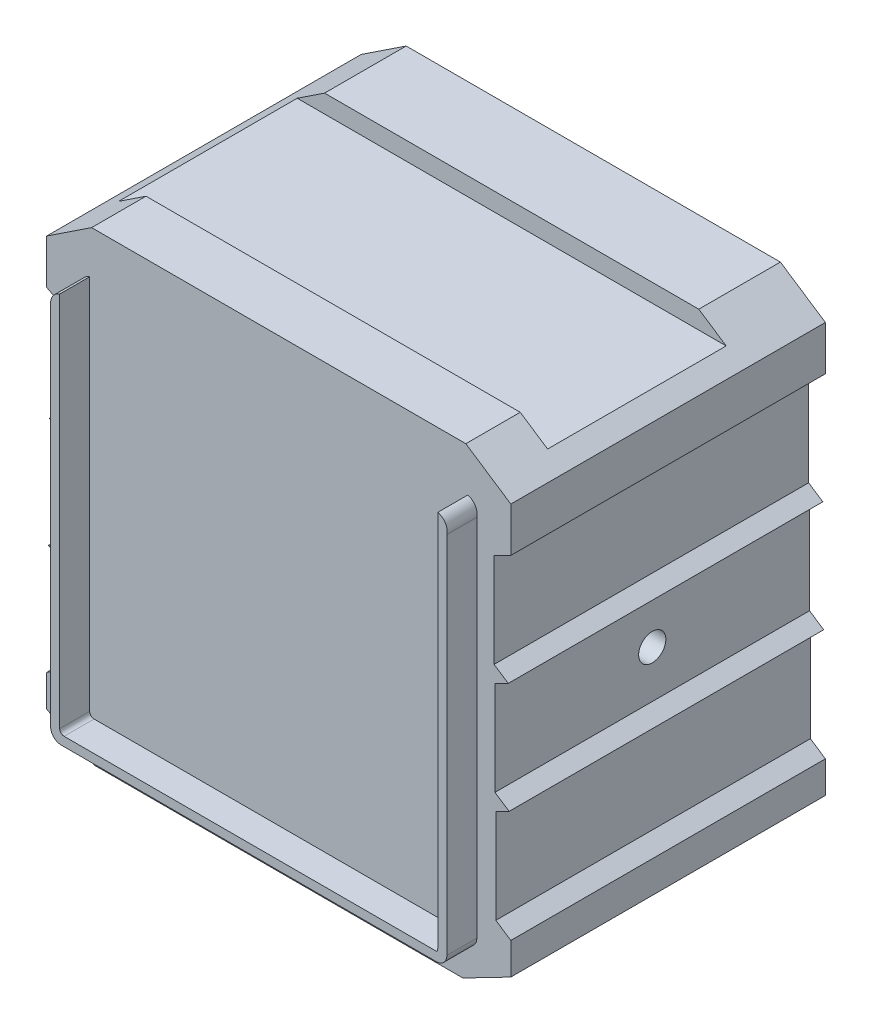
SolidWorks part; units mm, degrees
material "1060 Alloy"
ref_plane "Front" through (0, 0, 0) normal (0, 0, 1) x (1, 0, 0)
ref_plane "Top" through (0, 0, 0) normal (0, 1, 0) x (1, 0, 0)
ref_plane "Right" through (0, 0, 0) normal (1, 0, 0) x (0, 0, -1)
sketch "Sketch1" plane through (0, 0, 0) normal (0, 0, 1) x (1, 0, 0)
  line L0 (-103.1895, 0) -> (103.1895, 0)
  line L1 (103.1895, 0) -> (128, -16.4326)
  line L2 (128, -16.4326) -> (128, -40.963)
  line L3 (128, -40.963) -> (118.7742, -45.6193)
  line L4 (118.7742, -45.6193) -> (118.7742, -97.6193)
  line L5 (118.7742, -97.6193) -> (126.5833, -102.7916)
  line L6 (126.5833, -102.7916) -> (119.254, -106.4908)
  line L7 (119.254, -106.4908) -> (119.254, -158.4908)
  line L8 (119.254, -158.4908) -> (127.0632, -163.663)
  line L9 (127.0632, -163.663) -> (119.7339, -167.3622)
  line L10 (119.7339, -167.3622) -> (119.7339, -219.3622)
  line L11 (119.7339, -219.3622) -> (128, -224.837)
  line L12 (128, -224.837) -> (128, -242.3453)
  line L13 (128, -242.3453) -> (101.5588, -256)
  line L14 (101.5588, -256) -> (-101.5588, -256)
  line L15 (0, 0) -> (0, -256) construction
  line L16 (-128, -242.3453) -> (-101.5588, -256)
  line L17 (-128, -224.837) -> (-128, -242.3453)
  line L18 (-119.7339, -219.3622) -> (-128, -224.837)
  line L19 (-119.7339, -167.3622) -> (-119.7339, -219.3622)
  line L20 (-127.0632, -163.663) -> (-119.7339, -167.3622)
  line L21 (-119.254, -158.4908) -> (-127.0632, -163.663)
  line L22 (-119.254, -106.4908) -> (-119.254, -158.4908)
  line L23 (-126.5833, -102.7916) -> (-119.254, -106.4908)
  line L24 (-118.7742, -97.6193) -> (-126.5833, -102.7916)
  line L25 (-118.7742, -45.6193) -> (-118.7742, -97.6193)
  line L26 (-128, -40.963) -> (-118.7742, -45.6193)
  line L27 (-128, -16.4326) -> (-128, -40.963)
  line L28 (-103.1895, 0) -> (-128, -16.4326)
  dimension "D1" = 256
  dimension "D2" = 52
  dimension "D3" = 52
  dimension "D4" = 52
  dimension "D5" = 256
extrude "Boss-Extrude1" add sketch "Sketch1" along normal blind 173.478
sketch "Sketch3" plane through (0, 0, 173.478) normal (0, 0, 1) x (1, 0, 0)
  line L0 (-109.254, -30.7764) -> (-109.254, -233.135)
  line L1 (-103.389, -239) -> (103.389, -239)
  line L2 (109.254, -233.135) -> (109.254, -32.174)
  line L3 (104.254, -23.9952) -> (104.254, -231.7845)
  line L4 (103.7898, -234) -> (-101.83, -234)
  line L5 (-104.254, -231.576) -> (-104.254, -23.9952)
  line L6 (119.254, -158.4908) -> (119.254, -106.4908) construction
  line L7 (-119.254, -106.4908) -> (-119.254, -158.4908) construction
  line L8 (-101.5588, -256) -> (101.5588, -256) construction
  arc A0 (-109.254, -233.135) -> (-103.389, -239) centre (-103.389, -233.135) ccw
  arc A1 (103.389, -239) -> (109.254, -233.135) centre (103.389, -233.135) ccw
  arc A3 (104.254, -231.7845) -> (103.7898, -234) centre (98.7346, -231.7845) cw
  arc A4 (-101.83, -234) -> (-104.254, -231.576) centre (-101.83, -231.576) cw
  arc A5 (-109.254, -30.7764) -> (-104.254, -23.9952) centre (-102.1556, -30.7764) cw
  arc A6 (109.254, -32.174) -> (104.254, -23.9952) centre (102.6646, -30.5846) ccw
  dimension "D1" = 10
  dimension "D2" = 10
  dimension "D3" = 5
  dimension "D4" = 5
  dimension "D5" = 5
  dimension "D6" = 17
extrude "Boss-Extrude2" add sketch "Sketch3" along normal blind 16.522
sketch "Sketch5" plane through (0, 0, 0) normal (0, 1, 0) x (1, 0, 0)
  line L0 (-128, -173.478) -> (-128, 0) construction
  line L1 (-128, -143.478) -> (128, -143.478)
  line L2 (-128, -143.478) -> (-128, -45)
  line L3 (-128, -45) -> (128, -45)
  line L4 (128, -143.478) -> (128, -45)
  line L5 (128, -173.478) -> (128, 0) construction
  line L7 (103.7898, -173.478) -> (-101.83, -173.478) construction
  line L8 (103.1895, 0) -> (-103.1895, 0) construction
  dimension "D1" = 30
  dimension "D2" = 45
extrude "Cut-Extrude3" cut sketch "Sketch5" against normal blind 10
sketch "Sketch6" plane through (0, 0, 173.478) normal (0, 0, 1) x (1, 0, 0)
  line L0 (-17.4423, -269.8438) -> (292.5577, -269.8438) construction
sketch "Sketch7" plane through (119.254, 0, 0) normal (1, 0, 0) x (0, 0, -1)
  line L0 (0, -158.4908) -> (0, -106.4908) construction
  line L1 (-173.478, -106.4908) -> (0, -106.4908) construction
  circle A0 centre (-86.739, -132.4908) radius 7.5
  point P4 (0, -132.4908)
  point P7 (-86.739, -106.4908)
  dimension "D1" = 15
extrude "Cut-Extrude4" cut sketch "Sketch7" against normal through all
